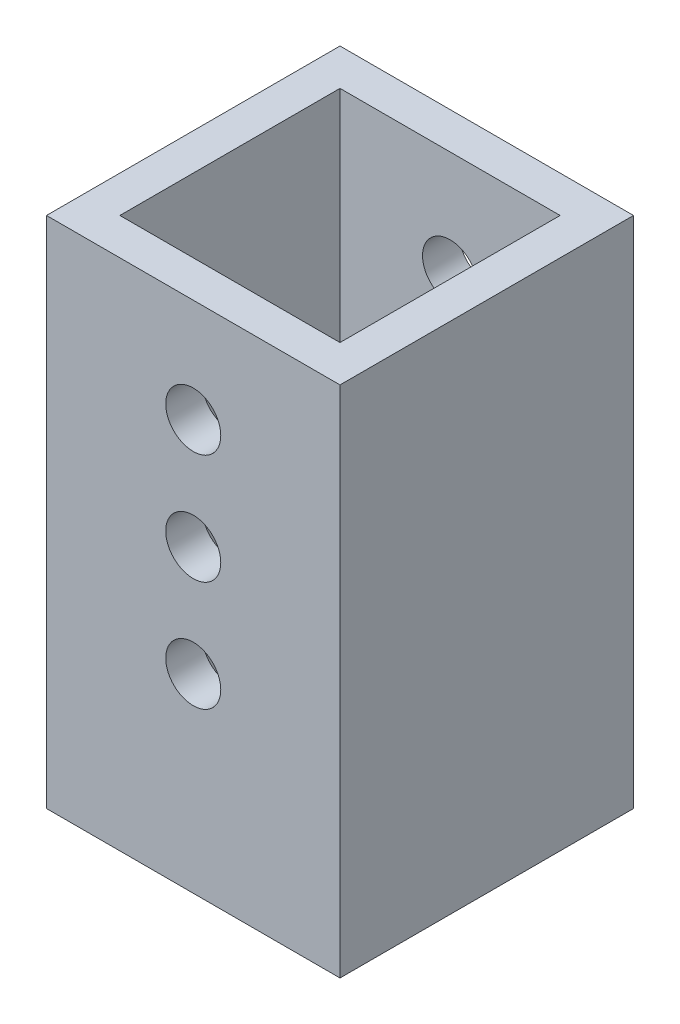
SolidWorks part; units mm, degrees
ref_plane "Front Plane" through (0, 0, 0) normal (0, 0, 1) x (1, 0, 0)
ref_plane "Top Plane" through (0, 0, 0) normal (0, 1, 0) x (1, 0, 0)
ref_plane "Right Plane" through (0, 0, 0) normal (1, 0, 0) x (0, 0, -1)
sketch "Sketch1" plane through (0, 0, 0) normal (0, 1, 0) x (1, 0, 0)
  line L1 (-25.4, 25.4) -> (25.4, 25.4)
  line L2 (-25.4, 25.4) -> (-25.4, -25.4)
  line L3 (-25.4, -25.4) -> (25.4, -25.4)
  line L4 (25.4, 25.4) -> (25.4, -25.4)
  dimension "D1" = 25.4
  dimension "D2" = 25.4
  dimension "D3" = 25.4
  dimension "D4" = 25.4
extrude "Boss-Extrude1" add sketch "Sketch1" along normal blind 88.9
sketch "Sketch2" plane through (0, 88.9, 0) normal (0, 1, 0) x (1, 0, 0)
  line L0 (25.4, 25.4) -> (-25.4, 25.4) construction
  line L1 (19.05, 19.05) -> (-19.05, 19.05)
  line L2 (19.05, 19.05) -> (19.05, -19.05)
  line L3 (19.05, -19.05) -> (-19.05, -19.05)
  line L4 (-19.05, 19.05) -> (-19.05, -19.05)
  line L5 (19.05, 19.05) -> (-19.05, -19.05) construction
  line L6 (19.05, -19.05) -> (-19.05, 19.05) construction
  line L7 (25.4, -25.4) -> (25.4, 25.4) construction
  point P0 (0, 0)
  dimension "D1" = 6.35
  dimension "D2" = 6.35
extrude "Cut-Extrude1" cut sketch "Sketch2" against normal through all
sketch "Sketch3" plane through (0, 0, 0) normal (0, -1, 0) x (-1, 0, 0)
  line L1 (19.05, -19.05) -> (-19.05, -19.05)
  line L2 (19.05, -19.05) -> (19.05, 19.05)
  line L3 (19.05, 19.05) -> (-19.05, 19.05)
  line L4 (-19.05, -19.05) -> (-19.05, 19.05)
extrude "Boss-Extrude2" add sketch "Sketch3" against normal blind 7.62
sketch "Sketch4" plane through (0, 0, 0) normal (0, -1, 0) x (-1, 0, 0)
  circle A0 centre (0, 0) radius 6.35
  dimension "D1" = 12.7
extrude "Boss-Extrude3" add sketch "Sketch4" along normal blind 19.05
sketch "Sketch6" plane through (0, 0, 25.4) normal (0, 0, 1) x (1, 0, 0)
  line L0 (25.4, 88.9) -> (25.4, 0) construction
  line L2 (-25.4, 88.9) -> (25.4, 88.9) construction
  line L3 (-25.4, 88.9) -> (-25.4, 0) construction
  circle A0 centre (0, 70.9773) radius 4.7625
  circle A1 centre (0, 51.9273) radius 4.7625
  circle A2 centre (0, 32.8773) radius 4.7625
  dimension "D4" = 19.05
  dimension "D5" = 9.525
  dimension "D6" = 9.525
  dimension "D7" = 9.525
  dimension "D8" = 25.4
  dimension "D2" = 17.9227
  dimension "D3" = 19.05
  dimension "D9" = 25.4
  dimension "D12" = 25.4
extrude "Cut-Extrude2" cut sketch "Sketch6" against normal through all
